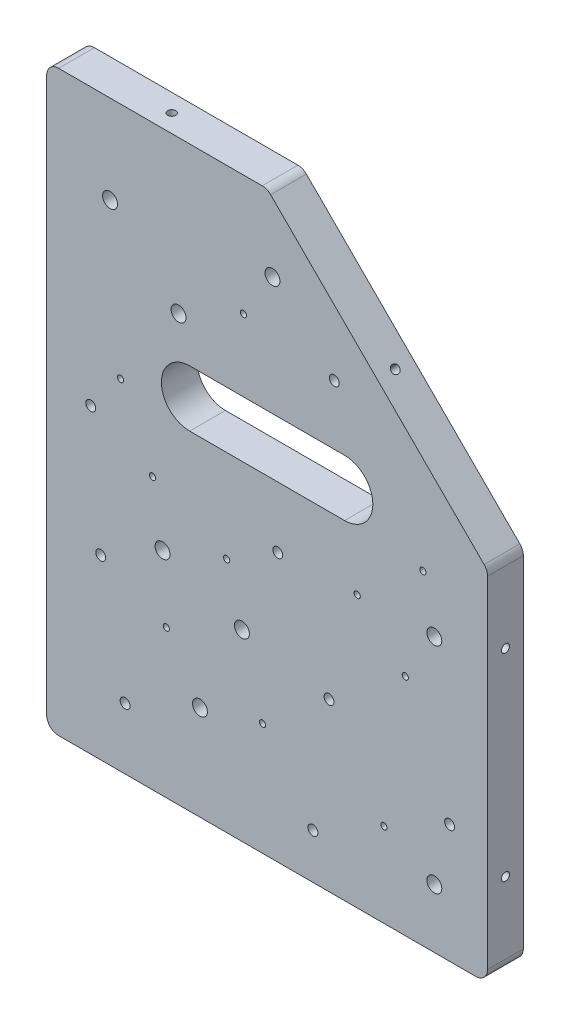
SolidWorks part; units mm, degrees
material "1060 Alloy"
ref_plane "Front Plane" through (0, 0, 0) normal (0, 0, 1) x (1, 0, 0)
ref_plane "Top Plane" through (0, 0, 0) normal (0, 1, 0) x (1, 0, 0)
ref_plane "Right Plane" through (0, 0, 0) normal (1, 0, 0) x (0, 0, -1)
sketch "Sketch1" plane through (0, 0, 0) normal (0, 0, 1) x (1, 0, 0)
  line L1 (0, 0) -> (370, 0)
  line L2 (0, 0) -> (0, 300)
  line L4 (370, 0) -> (370, 300)
  line L5 (185, 485) -> (370, 300)
  line L6 (120, 300) -> (250, 300) construction
  line L9 (185, 485) -> (185, 0) construction
  line L12 (120, 323.7101) -> (250, 323.7101)
  line L13 (120, 276.2899) -> (250, 276.2899)
  line L14 (185, 485) -> (0, 485)
  line L15 (0, 485) -> (0, 300)
  arc A4 (120, 323.7101) -> (120, 276.2899) centre (120, 300) ccw
  arc A5 (250, 276.2899) -> (250, 323.7101) centre (250, 300) ccw
  point P8 (185, 300)
  dimension "D1" = 370
  dimension "D2" = 300
  dimension "D3" = 300
extrude "Boss-Extrude2" add sketch "Sketch1" along normal blind 30
fillet "Fillet2" radius 10 2 edges at (0, 0, 15) (370, 0, 15)
fillet "Fillet3" radius 10 3 edges at (370, 300, 15) (0, 485, 15) (185, 485, 15)
sketch "Sketch6" plane through (0, 0, 30) normal (0, 0, 1) x (1, 0, 0)
  point P0 (300.971, 188.5529)
  point P2 (181.1557, 94.3665)
  point P4 (100.4245, 123.8398)
  point P6 (151.0416, 198.8045)
  point P8 (260.6054, 227.637)
  point P10 (283.0307, 70.6597)
  point P12 (88.8914, 227.637)
  point P14 (165.1376, 383.9736)
  point P16 (315.7076, 272.4877)
  point P18 (61.981, 285.3022)
  point P23 (88.8914, 227.637)
hole_wizard "Tap Drill for M5 Helicoil1" positions "Sketch6" profile "Sketch5" hole size "M5x0.8" standard "DIN" end condition through all
sketch "Sketch5" plane through (300.971, 188.5529, 30) normal (1, 0, 0) x (0, -1, 0)
  line L0 (0, 0) -> (0, 30)
  line L1 (0, 30) -> (2.6, 30)
  line L2 (2.6, 30) -> (2.6, 0)
  line L5 (2.6, 0) -> (0, 0)
  line L11 (0, -6.35) -> (0, 107.95) construction
  dimension "Thru Hole Dia." = 5.2
  dimension "Thru Hole Depth" = 30
sketch "Sketch9" plane through (0, 0, 30) normal (0, 0, 1) x (1, 0, 0)
  point P0 (65.8254, 51.438)
  point P2 (45.3222, 148.828)
  point P4 (236.8986, 139.8579)
  point P6 (241.3837, 373.722)
  point P8 (338.133, 99.4923)
  point P10 (223.4434, 37.9828)
  point P12 (193.9701, 225.0741)
  point P14 (36.9928, 253.266)
hole_wizard "Tap Drill for M8 Helicoil4" positions "Sketch9" profile "Sketch8" hole size "M8x1.25" standard "DIN" end condition through all
sketch "Sketch8" plane through (65.8254, 51.438, 30) normal (1, 0, 0) x (0, -1, 0)
  line L0 (0, 0) -> (0, 30)
  line L1 (0, 30) -> (4.15, 30)
  line L2 (4.15, 30) -> (4.15, 0)
  line L5 (4.15, 0) -> (0, 0)
  line L11 (0, -6.35) -> (0, 107.95) construction
  dimension "Thru Hole Dia." = 8.3
  dimension "Thru Hole Depth" = 30
sketch "Sketch12" plane through (0, 0, 30) normal (0, 0, 1) x (1, 0, 0)
  point P0 (163.8561, 153.9538)
  point P2 (325.3185, 49.5614)
  point P4 (128.6163, 79.6298)
  point P6 (189.4851, 423.0578)
  point P8 (110.676, 357.0632)
  point P10 (97.2208, 178.3013)
  point P12 (325.3185, 229.5592)
  point P13 (53.1905, 410.8867)
  point P14 (325.3185, 49.5614)
hole_wizard "Tap Drill for M12 Helicoil1" positions "Sketch12" profile "Sketch11" hole size "M12x1.75" standard "DIN" end condition through all
sketch "Sketch11" plane through (163.8561, 153.9538, 30) normal (1, 0, 0) x (0, -1, 0)
  line L0 (0, 0) -> (0, 30)
  line L1 (0, 30) -> (6.25, 30)
  line L2 (6.25, 30) -> (6.25, 0)
  line L5 (6.25, 0) -> (0, 0)
  line L11 (0, -6.35) -> (0, 107.95) construction
  dimension "Thru Hole Dia." = 12.5
  dimension "Thru Hole Depth" = 30
sketch "Sketch14" plane through (0, 0, 0) normal (0, -1, 0) x (-1, 0, 0)
  line L0 (-10, -15) -> (-65, -15) construction
  line L1 (-10, -30) -> (-10, 0) construction
  line L2 (-360, -15) -> (-315, -15) construction
  line L3 (-360, 0) -> (-360, -30) construction
  point P1 (-65, -15)
  point P5 (-315, -15)
  point P14 (-315, -15)
  point P16 (-65, -15)
  dimension "D1" = 55
  dimension "D2" = 45
hole_wizard "Tap Drill for M8 Tap1" positions "Sketch14" profile "Sketch17" hole size "M8" standard "DIN"
sketch "Sketch17" plane through (65, 0, 15) normal (1, 0, 0) x (0, 0, -1)
  line L0 (0, 0) -> (0, 27.0429)
  line L1 (0, 27.0429) -> (3.4, 25)
  line L2 (3.4, 25) -> (3.4, 0)
  line L5 (3.4, 0) -> (0, 0)
  line L10 (0, 27.0429) -> (-3.4, 25) construction
  line L11 (0, -6.35) -> (0, 107.95) construction
  dimension "Hole Dia." = 6.8
  dimension "Hole Depth" = 25
  dimension "Drill Angle" = 118
cosmetic thread "Cosmetic Thread11" parameters "D2"=8
cosmetic thread "Cosmetic Thread12" parameters "D2"=8
sketch "Sketch36" plane through (335, 335, 0) normal (0.7071, 0.7071, 0) x (0.7071, -0.7071, 0)
  line L0 (-207.9899, -15) -> (45.3553, -15) construction
  line L1 (-207.9899, 0) -> (-207.9899, -30) construction
  line L2 (45.3553, -30) -> (45.3553, 0) construction
  point P12 (-81.3173, -15)
hole_wizard "Tap Drill for M8 Tap2" positions "Sketch36" profile "Sketch37" hole size "M8" standard "DIN"
sketch "Sketch37" plane through (277.5, 392.5, 15) normal (0, 0, 1) x (-0.7071, 0.7071, 0)
  line L0 (0, 0) -> (0, 27.0429)
  line L1 (0, 27.0429) -> (3.4, 25)
  line L2 (3.4, 25) -> (3.4, 0)
  line L5 (3.4, 0) -> (0, 0)
  line L10 (0, 27.0429) -> (-3.4, 25) construction
  line L11 (0, -6.35) -> (0, 107.95) construction
  dimension "Hole Dia." = 6.8
  dimension "Hole Depth" = 25
  dimension "Drill Angle" = 118
cosmetic thread "Cosmetic Thread1" parameters "D2"=8
sketch "Sketch38" plane through (0, 485, 0) normal (0, 1, 0) x (1, 0, 0)
  line L0 (10, -15) -> (90, -15) construction
  line L1 (10, 0) -> (10, -30) construction
  point P1 (90, -15)
  point P9 (90, -15)
  dimension "D1" = 80
hole_wizard "Tap Drill for M8 Tap4" positions "Sketch38" profile "Sketch39" hole size "M8" standard "DIN"
sketch "Sketch39" plane through (90, 485, 15) normal (1, 0, 0) x (0, 0, 1)
  line L0 (0, 0) -> (0, 27.0429)
  line L1 (0, 27.0429) -> (3.4, 25)
  line L2 (3.4, 25) -> (3.4, 0)
  line L5 (3.4, 0) -> (0, 0)
  line L10 (0, 27.0429) -> (-3.4, 25) construction
  line L11 (0, -6.35) -> (0, 107.95) construction
  dimension "Hole Dia." = 6.8
  dimension "Hole Depth" = 25
  dimension "Drill Angle" = 118
cosmetic thread "Cosmetic Thread9" parameters "D2"=8
sketch "Sketch40" plane through (370, 0, 0) normal (1, 0, 0) x (0, 0, -1)
  line L0 (-15, 10) -> (-15, 70) construction
  line L1 (-30, 10) -> (0, 10) construction
  line L2 (-15, 295.8579) -> (-15, 235.8579) construction
  line L3 (0, 295.8579) -> (-30, 295.8579) construction
  point P1 (-15, 70)
  point P5 (-15, 235.8579)
  point P14 (-15, 70)
  point P16 (-15, 235.8579)
  dimension "D1" = 60
  dimension "D2" = 60
hole_wizard "Tap Drill for M8 Tap5" positions "Sketch40" profile "Sketch41" hole size "M8" standard "DIN"
sketch "Sketch41" plane through (370, 235.8579, 15) normal (0, 1, 0) x (0, 0, -1)
  line L0 (0, 0) -> (0, 27.0429)
  line L1 (0, 27.0429) -> (3.4, 25)
  line L2 (3.4, 25) -> (3.4, 0)
  line L5 (3.4, 0) -> (0, 0)
  line L10 (0, 27.0429) -> (-3.4, 25) construction
  line L11 (0, -6.35) -> (0, 107.95) construction
  dimension "Hole Dia." = 6.8
  dimension "Hole Depth" = 25
  dimension "Drill Angle" = 118
cosmetic thread "Cosmetic Thread8" parameters "D2"=8
cosmetic thread "Cosmetic Thread10" parameters "D2"=8
